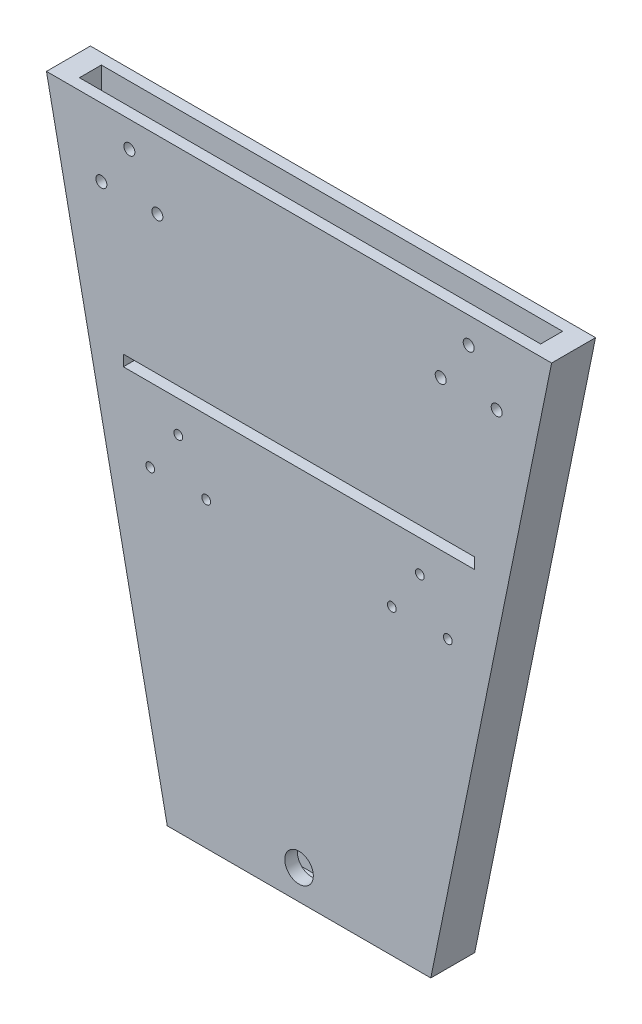
SolidWorks part; units mm, degrees
ref_plane "前视基准面" through (0, 0, 0) normal (0, 0, 1) x (1, 0, 0)
ref_plane "上视基准面" through (0, 0, 0) normal (0, 1, 0) x (1, 0, 0)
ref_plane "右视基准面" through (0, 0, 0) normal (1, 0, 0) x (0, 0, -1)
other "Configuration Table"
sketch "草图1" plane through (0, 0, 0) normal (0, 0, 1) x (1, 0, 0)
  line L0 (0, 0) -> (0, 50.6623) construction
  line L1 (-115, 220) -> (115, 220)
  line L2 (-60, -50) -> (60, -50)
  line L3 (-115, 220) -> (-60, -50)
  line L4 (115, 220) -> (60, -50)
  point P6 (0, 220)
  point P7 (0, -50)
  dimension "D1" = 230
  dimension "D2" = 120
  dimension "D3" = 270
  dimension "D4" = 50
extrude "凸台-拉伸1" add sketch "草图1" along normal blind 20
sketch "草图3" plane through (0, 220, 0) normal (0, 1, 0) x (1, 0, 0)
  line L0 (115, -20) -> (-115, -20) construction
  line L1 (-105, -5) -> (105, -5)
  line L2 (-105, -5) -> (-105, -15)
  line L3 (-105, -15) -> (105, -15)
  line L4 (105, -5) -> (105, -15)
  line L5 (-105, -5) -> (105, -15) construction
  line L6 (-105, -15) -> (105, -5) construction
  line L8 (-115, -20) -> (-115, 0) construction
  point P4 (0, -10)
  dimension "D1" = 210
  dimension "D2" = 10
  dimension "D3" = 10
  dimension "D4" = 115
extrude "切除-拉伸1" cut sketch "草图3" against normal blind 15
sketch "草图4" plane through (0, 0, 20) normal (0, 0, 1) x (1, 0, 0)
  line L0 (-96.3631, 128.51) -> (96.3631, 128.51)
  line L1 (-115, 220) -> (-60, -50) construction
  line L2 (60, -50) -> (115, 220) construction
  line L3 (-94.3261, 118.51) -> (94.3261, 118.51)
  line L4 (115, 220) -> (-115, 220) construction
  line L5 (0, 220) -> (0, -87.5938) construction
  line L6 (-80, 126.01) -> (80, 126.01)
  line L7 (-80, 126.01) -> (-80, 121.01)
  line L8 (-80, 121.01) -> (80, 121.01)
  line L9 (80, 126.01) -> (80, 121.01)
  line L10 (-80, 126.01) -> (80, 121.01) construction
  line L11 (-80, 121.01) -> (80, 126.01) construction
  point P14 (0, 123.51)
  dimension "D1" = 10
  dimension "D2" = 91.49
  dimension "D3" = 160
  dimension "D4" = 5
  dimension "D5" = 5
extrude "切除-拉伸2" cut sketch "草图4" against normal blind 10 contours L9 L6 L7 L8
sketch "草图5" plane through (0, 0, 20) normal (0, 0, 1) x (1, 0, 0)
  line L0 (0, 220) -> (0, -61.0662) construction
  line L1 (-96.3631, 128.51) -> (96.3631, 128.51)
  line L2 (-115, 220) -> (-60, -50) construction
  line L3 (60, -50) -> (115, 220) construction
  line L4 (-94.3261, 118.51) -> (94.3261, 118.51)
  line L5 (115, 220) -> (-115, 220) construction
  circle A0 centre (-77.25, 208.1426) radius 2.5
  circle A1 centre (-90, 189) radius 2.5
  circle A2 centre (-64.5, 189) radius 2.5
  circle A3 centre (-55, 106.6526) radius 2
  circle A4 centre (-67.75, 87.51) radius 2
  circle A5 centre (-42.25, 87.51) radius 2
  circle A6 centre (42.25, 87.51) radius 2
  circle A7 centre (67.75, 87.51) radius 2
  circle A8 centre (55, 106.6526) radius 2
  circle A9 centre (64.5, 189) radius 2.5
  circle A10 centre (90, 189) radius 2.5
  circle A11 centre (77.25, 208.1426) radius 2.5
  point P37 (0, 0)
  dimension "D8" = 5
  dimension "D9" = 5
  dimension "D10" = 5
  dimension "D12" = 4
  dimension "D13" = 4
  dimension "D14" = 4
  dimension "D1" = 10
  dimension "D2" = 91.49
  dimension "D3" = 31
  dimension "D4" = 31
  dimension "D5" = 23
  dimension "D6" = 23
  dimension "D7" = 25.5
  dimension "D11" = 90
  dimension "D15" = 23
  dimension "D16" = 23
  dimension "D17" = 31
  dimension "D18" = 31
  dimension "D19" = 25.5
  dimension "D20" = 55
extrude "切除-拉伸3" cut sketch "草图5" against normal blind 10 contours A0 | A2 | A1 | A11 | A10 | A9 | A3 | A5 | A4 | A8 | A6 | A7
ref_plane "基准面1" through (0, 0, 10) normal (0, 0, -1) x (-1, 0, 0)
sketch "草图6" plane through (0, 0, 10) normal (0, 0, -1) x (-1, 0, 0)
  line L0 (0, 220) -> (0, -76.53) construction
  line L1 (0, -49.69) -> (18.0161, -49.69)
  line L2 (-115, 220) -> (115, 220) construction
  line L3 (18.0161, -49.69) -> (11.7816, -23.29)
  line L4 (0, -23.29) -> (11.7816, -23.29)
  arc A0 (0, -23.29) -> (0, -49.69) centre (0, -36.49) ccw
  dimension "D2" = 26.4
  dimension "D1" = 256.49
  dimension "D3" = 14.5
extrude "切除-拉伸4" cut sketch "草图6" against normal mid plane 8.5
sketch "草图7" plane through (0, 0, 0) normal (0, 0, -1) x (-1, 0, 0)
  line L0 (0, 220) -> (0, -74.3263) construction
  line L2 (-115, 220) -> (115, 220) construction
  line L7 (60, -50) -> (115, 220)
  line L8 (-60, -50) -> (60, -50)
  line L9 (-115, 220) -> (-60, -50)
  line L10 (115, 220) -> (-115, 220)
  line L11 (60, -50) -> (115, 220)
  line L12 (-60, -50) -> (60, -50)
  line L13 (-115, 220) -> (-60, -50)
  line L14 (115, 220) -> (-115, 220)
  circle A0 centre (0, -36.49) radius 6.5
  dimension "D2" = 13
  dimension "D1" = 256.49
  dimension "D3" = 0
sketch "草图8" plane through (0, 0, 20) normal (0, 0, 1) x (1, 0, 0)
  line L4 (-115, 220) -> (-60, -50)
  line L5 (-60, -50) -> (60, -50)
  line L6 (60, -50) -> (115, 220)
  line L7 (115, 220) -> (-115, 220)
  line L8 (-115, 220) -> (-60, -50)
  line L9 (-60, -50) -> (60, -50)
  line L10 (60, -50) -> (115, 220)
  line L11 (115, 220) -> (-115, 220)
  circle A0 centre (0, -36.49) radius 6.5 construction
  circle A1 centre (0, -36.49) radius 6.5
  circle A2 centre (0, -36.49) radius 6.5
  dimension "D1" = 0
extrude "切除-拉伸6" cut sketch "草图8" against normal blind 15 contours A1
